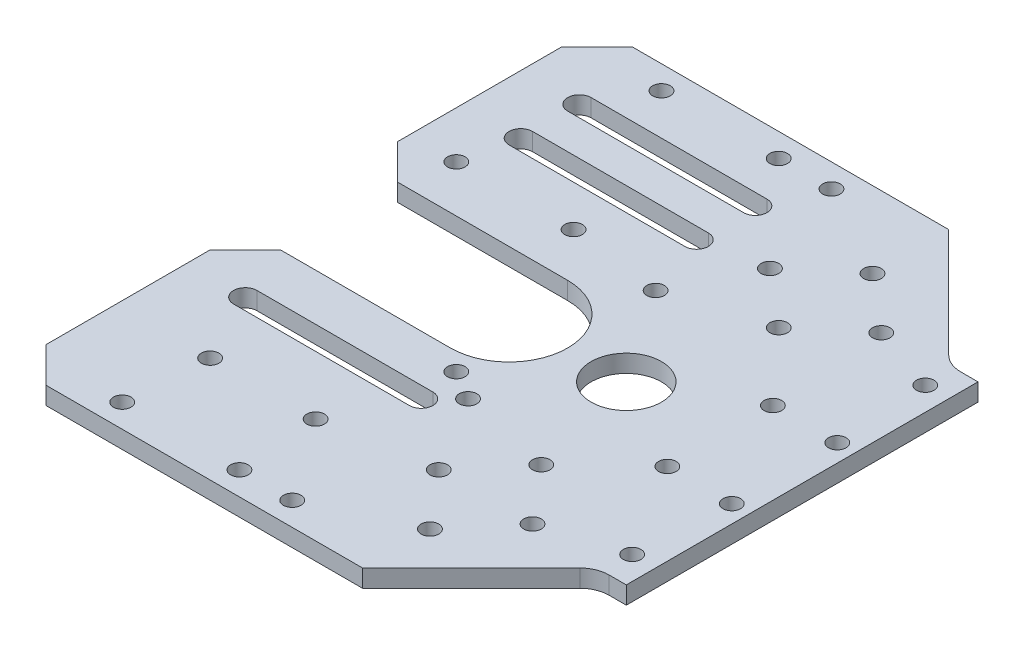
SolidWorks part; units mm, degrees
material "Thornel Mat VMA"
ref_plane "前视基准面" through (0, 0, 0) normal (0, 0, 1) x (1, 0, 0)
ref_plane "上视基准面" through (0, 0, 0) normal (0, 1, 0) x (1, 0, 0)
ref_plane "右视基准面" through (0, 0, 0) normal (1, 0, 0) x (0, 0, -1)
sketch "草图1" plane through (0, 0, 0) normal (0, 1, 0) x (1, 0, 0)
  line L0 (0, 0) -> (25, 0) construction
  line L1 (-54, 50) -> (0, 50)
  line L2 (-35, 0) -> (-35, -50) construction
  line L3 (0, 50) -> (20, 30)
  line L4 (20, 30) -> (25, 30)
  line L5 (20, -30) -> (25, -30)
  line L6 (0, 29) -> (0, -29) construction
  line L7 (-54, -50) -> (0, -50)
  line L8 (0, -50) -> (20, -30)
  line L9 (-54, 10) -> (-25, 10)
  line L10 (-25, -10) -> (-54, -10)
  line L11 (-35, 50) -> (-35, 0) construction
  line L12 (0, 0) -> (-60, 0) construction
  line L13 (-45, 46) -> (-25, 46) construction
  line L14 (-45, -46) -> (-25, -46) construction
  line L15 (-60, 44) -> (-60, 16)
  line L16 (25, 30) -> (25, -30)
  line L17 (-60, -16) -> (-60, -44)
  line L18 (0, 37) -> (0, 21) construction
  line L19 (-9.5, 29) -> (9.5, 29) construction
  line L20 (-8, -29) -> (8, -29) construction
  line L21 (0, -19.5) -> (0, -38.5) construction
  line L22 (22, 9) -> (22, -9) construction
  line L23 (-52, 18) -> (-32, 18) construction
  line L24 (-54, -10) -> (-60, -16)
  line L25 (-60, 16) -> (-54, 10)
  line L26 (-16, -16) -> (-16, -46) construction
  line L27 (-16, 16) -> (-16, 46) construction
  line L28 (-54, 50) -> (-60, 44)
  line L29 (-60, -44) -> (-54, -50)
  line L30 (-50, 37) -> (-20, 37) construction
  line L31 (-50, 39) -> (-20, 39)
  line L32 (-50, 35) -> (-20, 35)
  line L33 (-50, 27) -> (-20, 27) construction
  line L34 (-50, 29) -> (-20, 29)
  line L35 (-50, 25) -> (-20, 25)
  line L36 (-50, -20) -> (-20, -20) construction
  line L37 (-50, -18) -> (-20, -18)
  line L38 (-50, -22) -> (-20, -22)
  arc A0 (-25, 10) -> (-25, -10) centre (-25, 0) cw
  circle A1 centre (11, 9) radius 1.5
  circle A2 centre (11, -9) radius 1.5
  circle A3 centre (-44, -32) radius 1.5
  circle A4 centre (9.5, 29) radius 1.5
  circle A5 centre (0, 21) radius 1.5
  circle A6 centre (0, 29) radius 22.5 construction
  circle A7 centre (-9.5, 29) radius 1.5
  circle A8 centre (0, 37) radius 1.5
  circle A9 centre (0, -29) radius 22.5 construction
  circle A10 centre (-26, -32) radius 1.5
  circle A11 centre (0, -38.5) radius 1.5
  circle A12 centre (22, -9) radius 1.5
  circle A13 centre (22, 9) radius 1.5
  circle A14 centre (-8, -29) radius 1.5
  circle A15 centre (-21, -13) radius 1.5
  circle A16 centre (-52, 18) radius 1.5
  circle A17 centre (-32, 18) radius 1.5
  circle A18 centre (-25, 46) radius 1.5
  circle A19 centre (0, -19.5) radius 1.5
  circle A20 centre (-45, 46) radius 1.5
  circle A21 centre (8, -29) radius 1.5
  circle A22 centre (-25, -46) radius 1.5
  circle A23 centre (-45, -46) radius 1.5
  circle A24 centre (-16, -16) radius 1.5
  circle A25 centre (-16, -46) radius 1.5
  circle A26 centre (-16, 46) radius 1.5
  circle A27 centre (-16, 16) radius 1.5
  arc A28 (-50, 39) -> (-50, 35) centre (-50, 37) ccw
  arc A29 (-20, 35) -> (-20, 39) centre (-20, 37) ccw
  arc A30 (-50, 29) -> (-50, 25) centre (-50, 27) ccw
  arc A31 (-20, 25) -> (-20, 29) centre (-20, 27) ccw
  arc A32 (-50, -18) -> (-50, -22) centre (-50, -20) ccw
  arc A33 (-20, -22) -> (-20, -18) centre (-20, -20) ccw
  circle A34 centre (-5, 0) radius 6
  circle A35 centre (21, 25) radius 1.5
  circle A36 centre (21, -25) radius 1.5
  point P1 (-60, 10)
  point P13 (-60, -10)
  point P29 (0, 29)
  point P39 (-60, -50)
  point P47 (-60, 50)
  point P50 (-35, 46)
  point P55 (0, -29)
  point P86 (-35, 37)
  point P92 (-35, 27)
  point P99 (-35, -20)
  dimension "D4" = 100
  dimension "D7" = 45
  dimension "D9" = 18
  dimension "D10" = 3
  dimension "D17" = 14
  dimension "D19" = 18
  dimension "D25" = 46
  dimension "D26" = 13
  dimension "D27" = 18
  dimension "D28" = 8
  dimension "D3" = 3
  dimension "D6" = 60
  dimension "D18" = 18
  dimension "D24" = 45
  dimension "D31" = 19
  dimension "D33" = 30
  dimension "D34" = 3
  dimension "D37" = 30
  dimension "D38" = 2
  dimension "D40" = 10
  dimension "D41" = 10
  dimension "D36" = 4
  dimension "D23" = 18
  dimension "D16" = 3
  dimension "D22" = 3
  dimension "D30" = 3
  dimension "D42" = 12
  dimension "D43" = 5
  dimension "D44" = 3
  dimension "D45" = 4
  dimension "D46" = 50
  dimension "D8" = 58
  dimension "D11" = 5
  dimension "D12" = 20
  dimension "D13" = 60
  dimension "D14" = 35
  dimension "D15" = 25
  dimension "D20" = 4
  dimension "D21" = 20
  dimension "D29" = 20
  dimension "D32" = 16
  dimension "D35" = 16
  dimension "D58" = 22
extrude "凸台-拉伸1" add sketch "草图1" along normal blind 3
fillet "圆角1" radius 5 2 edges at (20, 1.5, -30) (20, 1.5, 30)
